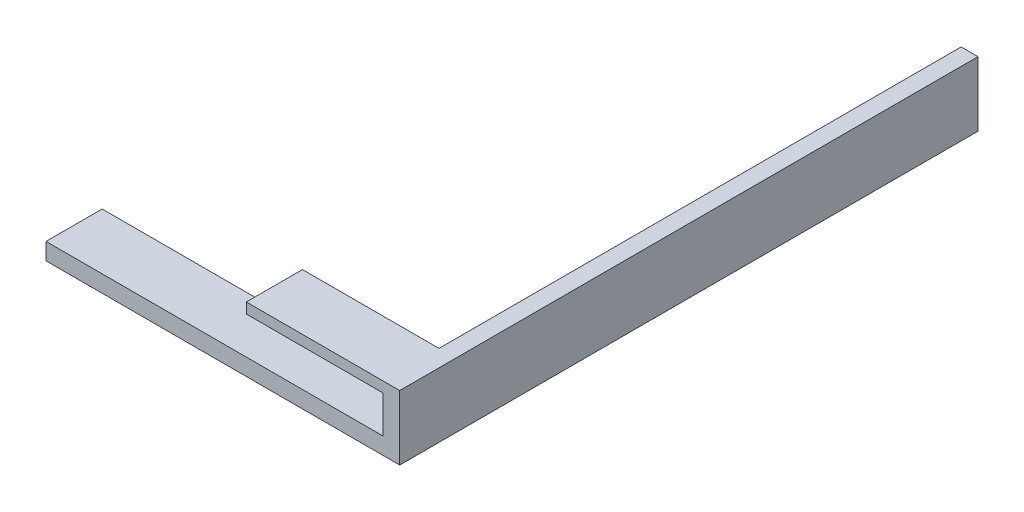
SolidWorks part; units mm, degrees
ref_plane "前视基准面" through (0, 0, 0) normal (0, 0, 1) x (1, 0, 0)
ref_plane "上视基准面" through (0, 0, 0) normal (0, 1, 0) x (1, 0, 0)
ref_plane "右视基准面" through (0, 0, 0) normal (1, 0, 0) x (0, 0, -1)
other "Configuration Table"
sketch "草图1" plane through (0, 0, 0) normal (0, 1, 0) x (1, 0, 0)
  line L1 (-31.5, -5) -> (31.5, -5)
  line L2 (-31.5, -5) -> (-31.5, 5)
  line L3 (-31.5, 5) -> (31.5, 5)
  line L4 (31.5, -5) -> (31.5, 5)
  line L5 (-31.5, -5) -> (31.5, 5) construction
  line L6 (-31.5, 5) -> (31.5, -5) construction
  point P0 (0, 0)
  dimension "D1" = 10
  dimension "D2" = 63
extrude "凸台-拉伸1" add sketch "草图1" along normal blind 2
sketch "草图4" plane through (0, 2, 0) normal (0, 1, 0) x (1, 0, 0)
  line L0 (-31.5, -5) -> (31.5, -5) construction
  line L1 (31.5, 5) -> (29.5, 5)
  line L2 (31.5, 5) -> (31.5, -5)
  line L3 (31.5, -5) -> (29.5, -5)
  line L4 (29.5, 5) -> (29.5, -5)
  dimension "D1" = 2
extrude "凸台-拉伸2" add sketch "草图4" along normal blind 93
sketch "草图5" plane through (0, 2, 0) normal (0, 1, 0) x (1, 0, 0)
  line L4 (29.5, -5) -> (29.5, 5)
  line L5 (29.5, 5) -> (-31.5, 5)
  line L6 (-31.5, 5) -> (-31.5, -5)
  line L7 (-31.5, -5) -> (29.5, -5)
  line L8 (29.5, -5) -> (29.5, 5)
  line L9 (29.5, 5) -> (-31.5, 5)
  line L10 (-31.5, 5) -> (-31.5, -5)
  line L11 (-31.5, -5) -> (29.5, -5)
  dimension "D1" = 0
extrude "凸台-拉伸3" add sketch "草图5" along normal blind 1
sketch "草图6" plane through (29.5, 0, 0) normal (-1, 0, 0) x (0, 0, 1)
  line L4 (-5, 95) -> (-5, 3)
  line L5 (-5, 3) -> (5, 3)
  line L6 (5, 3) -> (5, 95)
  line L7 (5, 95) -> (-5, 95)
  line L8 (-5, 95) -> (-5, 3)
  line L9 (-5, 3) -> (5, 3)
  line L10 (5, 3) -> (5, 95)
  line L11 (5, 95) -> (-5, 95)
  dimension "D1" = 0
extrude "凸台-拉伸4" add sketch "草图6" along normal blind 1
sketch "草图7" plane through (0, 0, -5) normal (0, 0, -1) x (-1, 0, 0)
  line L0 (-28.5, 95) -> (-28.5, 3) construction
  line L1 (-31.5, 0) -> (-28.5, 0)
  line L2 (-31.5, 0) -> (-31.5, 10)
  line L3 (-31.5, 10) -> (-28.5, 10)
  line L4 (-28.5, 0) -> (-28.5, 10)
  dimension "D1" = 10
extrude "凸台-拉伸5" add sketch "草图7" along normal blind 93
sketch "草图10" plane through (28.5, 0, 0) normal (-1, 0, 0) x (0, 0, 1)
  line L1 (-5, 10) -> (21.5943, 10)
  line L2 (-5, 10) -> (-5, 111.5597)
  line L3 (-5, 111.5597) -> (21.5943, 111.5597)
  line L4 (21.5943, 10) -> (21.5943, 111.5597)
extrude "切除-拉伸1" cut sketch "草图10" against normal blind 93
sketch "草图11" plane through (0, 10, 0) normal (0, 1, 0) x (1, 0, 0)
  line L4 (28.5, 98) -> (28.5, -5)
  line L5 (28.5, -5) -> (31.5, -5)
  line L6 (31.5, -5) -> (31.5, 98)
  line L7 (31.5, 98) -> (28.5, 98)
  line L8 (28.5, 98) -> (28.5, -5)
  line L9 (28.5, -5) -> (31.5, -5)
  line L10 (31.5, -5) -> (31.5, 98)
  line L11 (31.5, 98) -> (28.5, 98)
  dimension "D1" = 0
extrude "凸台-拉伸6" add sketch "草图11" along normal blind 1.5
sketch "草图12" plane through (28.5, 0, 0) normal (-1, 0, 0) x (0, 0, 1)
  line L1 (5, 11.5) -> (-5, 11.5)
  line L2 (5, 11.5) -> (5, 7.6387)
  line L3 (5, 7.6387) -> (-5, 7.6387)
  line L4 (-5, 11.5) -> (-5, 7.6387)
  dimension "D1" = 3.8613
  dimension "D2" = 10
extrude "凸台-拉伸7" add sketch "草图12" along normal blind 20.32
sketch "草图13" plane through (8.18, 0, 0) normal (-1, 0, 0) x (0, 0, 1)
  line L4 (5, 7.6387) -> (5, 11.5)
  line L5 (5, 11.5) -> (-5, 11.5)
  line L6 (-5, 11.5) -> (-5, 7.6387)
  line L7 (-5, 7.6387) -> (5, 7.6387)
  line L8 (5, 7.6387) -> (5, 11.5)
  line L9 (5, 11.5) -> (-5, 11.5)
  line L10 (-5, 11.5) -> (-5, 7.6387)
  line L11 (-5, 7.6387) -> (5, 7.6387)
  dimension "D1" = 0
extrude "凸台-拉伸8" add sketch "草图13" along normal blind 4
sketch "草图14" plane through (0, 7.6387, 0) normal (0, -1, 0) x (1, 0, 0)
  line L4 (28.5, -5) -> (28.5, 5)
  line L5 (28.5, 5) -> (4.18, 5)
  line L6 (4.18, 5) -> (4.18, -5)
  line L7 (4.18, -5) -> (28.5, -5)
  line L8 (28.5, -5) -> (28.5, 5)
  line L9 (28.5, 5) -> (4.18, 5)
  line L10 (4.18, 5) -> (4.18, -5)
  line L11 (4.18, -5) -> (28.5, -5)
  dimension "D1" = 0
extrude "切除-拉伸2" cut sketch "草图14" against normal blind 2
